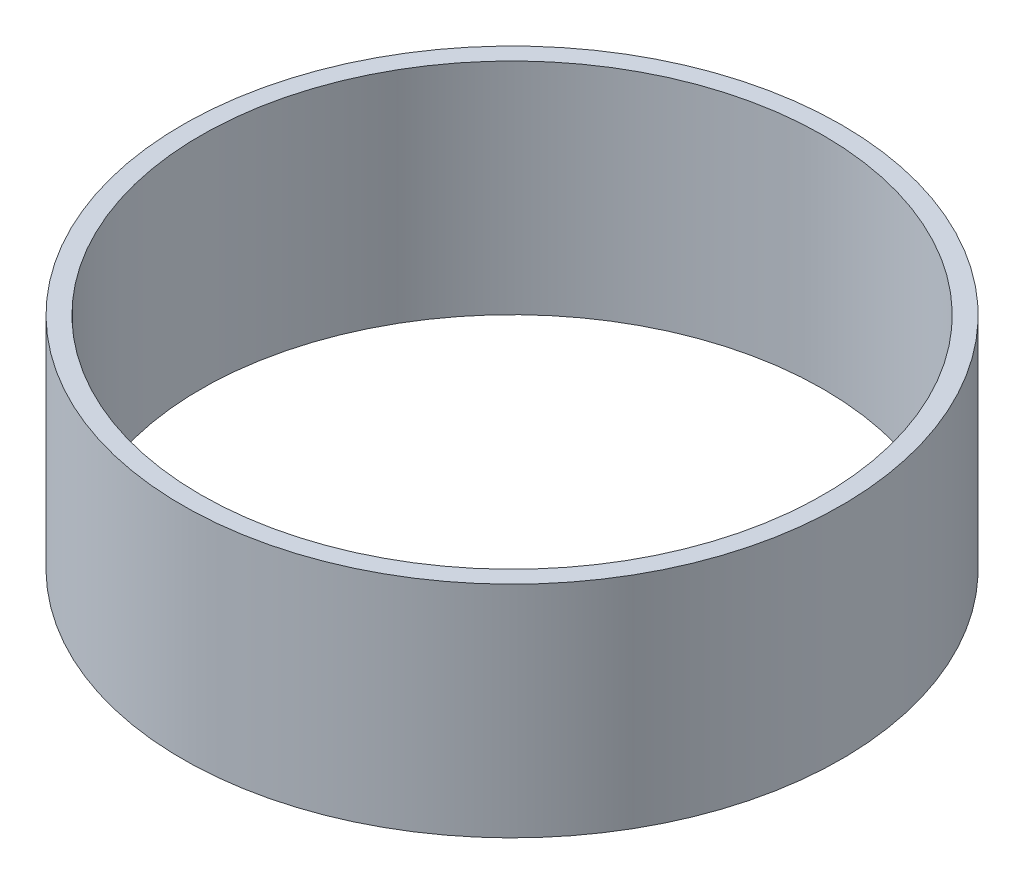
SolidWorks part; units mm, degrees
ref_plane "Front Plane" through (0, 0, 0) normal (0, 0, 1) x (1, 0, 0)
ref_plane "Top Plane" through (0, 0, 0) normal (0, 1, 0) x (1, 0, 0)
ref_plane "Right Plane" through (0, 0, 0) normal (1, 0, 0) x (0, 0, -1)
sketch "Sketch1" plane through (0, 0, 0) normal (0, 1, 0) x (1, 0, 0)
  circle A0 centre (0, 0) radius 1828.8
  circle A1 centre (0, 0) radius 1727.2
  dimension "D1" = 3657.6
  dimension "D2" = 3454.4
extrude "Boss-Extrude1" add sketch "Sketch1" along normal blind 1219.2
